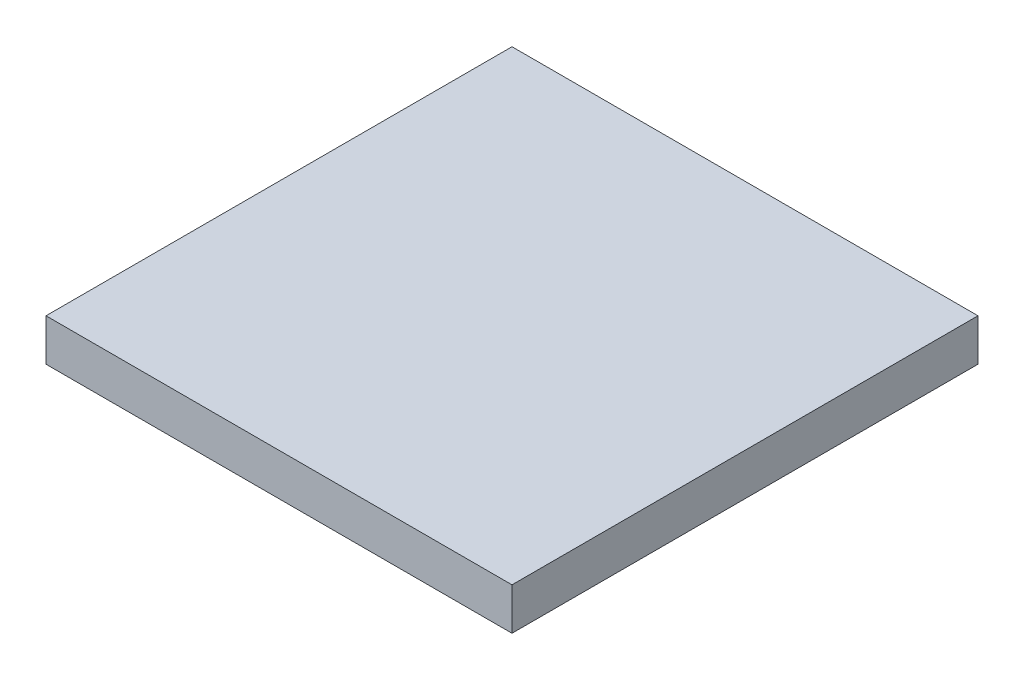
SolidWorks part; units mm, degrees
ref_plane "Front Plane" through (0, 0, 0) normal (0, 0, 1) x (1, 0, 0)
ref_plane "Top Plane" through (0, 0, 0) normal (0, 1, 0) x (1, 0, 0)
ref_plane "Right Plane" through (0, 0, 0) normal (1, 0, 0) x (0, 0, -1)
sketch "Sketch1" plane through (0, 0, 0) normal (0, 1, 0) x (1, 0, 0)
  line L1 (0, 0) -> (14.1, 0)
  line L2 (0, 0) -> (0, 14.1)
  line L3 (0, 14.1) -> (14.1, 14.1)
  line L4 (14.1, 0) -> (14.1, 14.1)
  dimension "D1" = 14.1
  dimension "D2" = 14.1
extrude "Boss-Extrude1" add sketch "Sketch1" along normal blind 1.27
